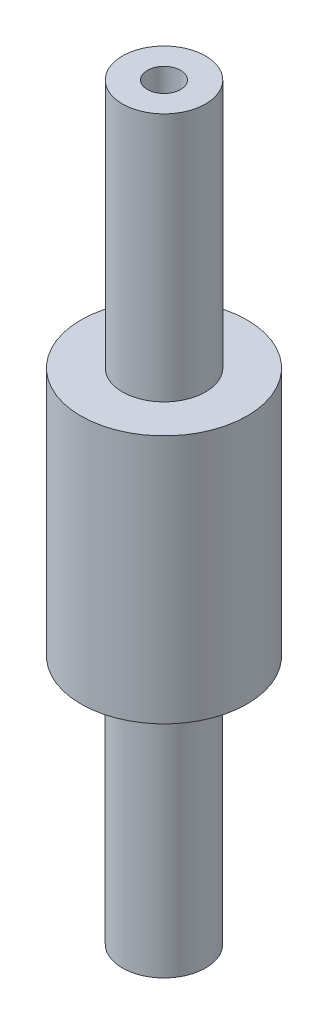
SolidWorks part; units mm, degrees
ref_plane "前视基准面" through (0, 0, 0) normal (0, 0, 1) x (1, 0, 0)
ref_plane "上视基准面" through (0, 0, 0) normal (0, 1, 0) x (1, 0, 0)
ref_plane "右视基准面" through (0, 0, 0) normal (1, 0, 0) x (0, 0, -1)
sketch "草图1" plane through (0, 0, 0) normal (0, 1, 0) x (1, 0, 0)
  circle A0 centre (0, 0) radius 10
  dimension "D1" = 20
extrude "凸台-拉伸1" add sketch "草图1" along normal blind 30
sketch "草图2" plane through (0, 30, 0) normal (0, 1, 0) x (1, 0, 0)
  circle A0 centre (0, 0) radius 5
extrude "凸台-拉伸2" add sketch "草图2" along normal blind 30
sketch "草图3" plane through (0, 0, 0) normal (0, -1, 0) x (-1, 0, 0)
  circle A0 centre (0, 0) radius 5
extrude "凸台-拉伸3" add sketch "草图3" along normal blind 30
sketch "草图4" plane through (0, 60, 0) normal (0, 1, 0) x (1, 0, 0)
  circle A0 centre (0, 0) radius 2
  dimension "D1" = 4
extrude "切除-拉伸1" cut sketch "草图4" against normal blind 20
sketch "草图5" plane through (0, -30, 0) normal (0, -1, 0) x (-1, 0, 0)
  circle A0 centre (0, 0) radius 2
  dimension "D1" = 4
extrude "切除-拉伸2" cut sketch "草图5" against normal blind 20
